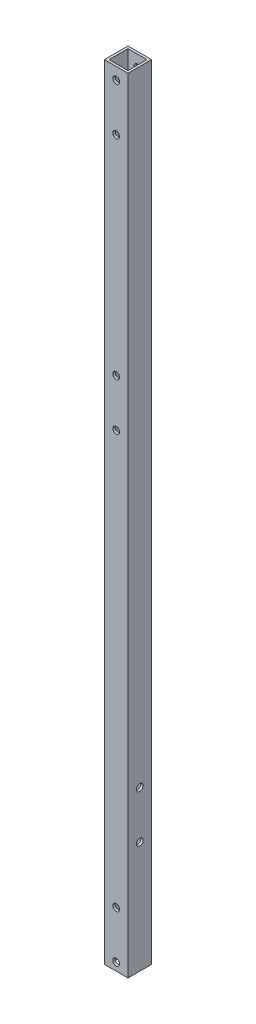
SolidWorks part; units mm, degrees
material "5052-H34"
ref_plane "正面" through (0, 0, 0) normal (0, 0, 1) x (1, 0, 0)
ref_plane "平面" through (0, 0, 0) normal (0, 1, 0) x (1, 0, 0)
ref_plane "右側面" through (0, 0, 0) normal (1, 0, 0) x (0, 0, -1)
sketch "ｽｹｯﾁ1" plane through (0, 0, 0) normal (0, 1, 0) x (1, 0, 0)
  line L1 (-7.5, 7.5) -> (7.5, 7.5)
  line L2 (-7.5, 7.5) -> (-7.5, -7.5)
  line L3 (-7.5, -7.5) -> (7.5, -7.5)
  line L4 (7.5, 7.5) -> (7.5, -7.5)
  line L5 (-7.5, 7.5) -> (7.5, -7.5) construction
  line L6 (-7.5, -7.5) -> (7.5, 7.5) construction
  point P0 (0, 0)
  dimension "D1" = 15
  dimension "D2" = 15
extrude "押し出し-薄板1" add sketch "ｽｹｯﾁ1" along normal blind 497.5 thin
sketch "ｽｹｯﾁ2" plane through (7.5, 0, 0) normal (1, 0, 0) x (0, 0, -1)
  line L0 (0, 0) -> (0, 181) construction
  line L1 (-7.5, 0) -> (7.5, 0) construction
  circle A0 centre (0, 181) radius 2.15 construction
  circle A1 centre (0, 151) radius 2.15 construction
  circle A2 centre (0, 71) radius 2.15
  circle A3 centre (0, 101) radius 2.15
  dimension "D1" = 4.3
  dimension "D2" = 71
  dimension "D3" = 30
  dimension "D4" = 50
  dimension "D5" = 30
extrude "ｶｯﾄ - 押し出し1" cut sketch "ｽｹｯﾁ2" against normal through all
sketch "ｽｹｯﾁ3" plane through (0, 0, 7.5) normal (0, 0, 1) x (1, 0, 0)
  line L0 (0, 0) -> (0, 35) construction
  line L1 (0, 497.5) -> (0, 297.5) construction
  line L2 (-7.5, 497.5) -> (7.5, 497.5) construction
  circle A0 centre (0, 35) radius 2.15
  circle A1 centre (0, 5) radius 2.15
  circle A2 centre (0, 297.5) radius 2.15
  circle A3 centre (0, 327.5) radius 2.15
  circle A4 centre (0, 490) radius 2.15
  circle A5 centre (0, 460) radius 2.15
  dimension "D1" = 4.3
  dimension "D5" = 4.3
  dimension "D2" = 5
  dimension "D3" = 30
  dimension "D4" = 192.5
  dimension "D6" = 7.5
  dimension "D7" = 30
  dimension "D8" = 30
extrude "ｶｯﾄ - 押し出し2" cut sketch "ｽｹｯﾁ3" against normal through all
